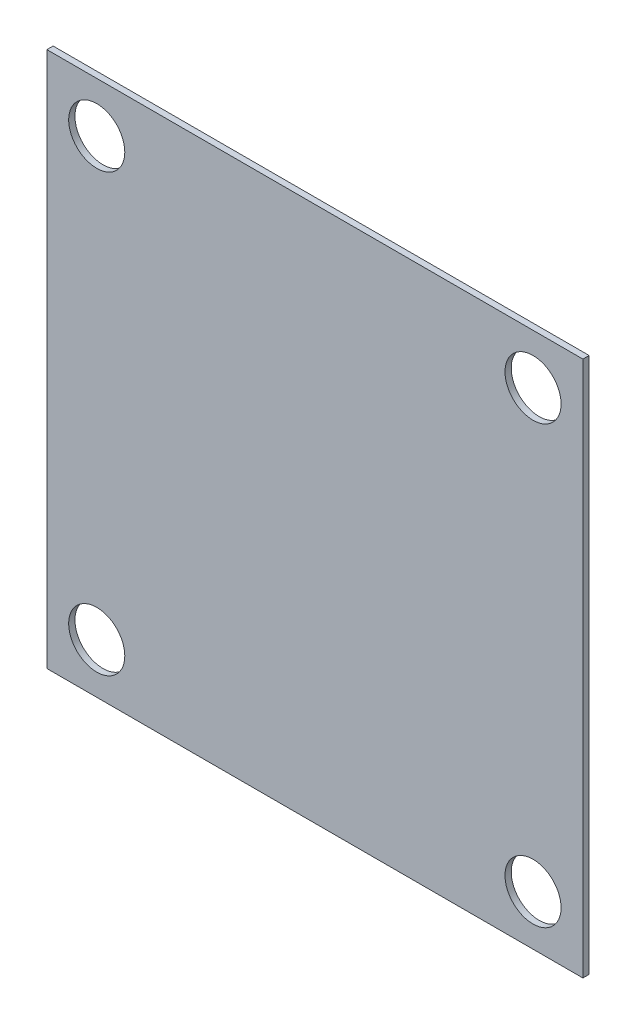
SolidWorks part; units mm, degrees
ref_plane "Front Plane" through (0, 0, 0) normal (0, 0, 1) x (1, 0, 0)
ref_plane "Top Plane" through (0, 0, 0) normal (0, 1, 0) x (1, 0, 0)
ref_plane "Right Plane" through (0, 0, 0) normal (1, 0, 0) x (0, 0, -1)
sketch "Sketch1" plane through (0, 0, 0) normal (0, 0, 1) x (1, 0, 0)
  line L1 (-35, -35) -> (35, -35) construction
  line L2 (-35, -35) -> (-35, 35) construction
  line L3 (-35, 35) -> (35, 35) construction
  line L4 (35, -35) -> (35, 35) construction
  line L5 (-35, -35) -> (35, 35) construction
  line L6 (-35, 35) -> (35, -35) construction
  line L7 (-43, -43) -> (43, -43)
  line L8 (-43, -43) -> (-43, 43)
  line L9 (-43, 43) -> (43, 43)
  line L10 (43, -43) -> (43, 43)
  line L11 (-43, -43) -> (43, 43) construction
  line L12 (-43, 43) -> (43, -43) construction
  circle A0 centre (35, 35) radius 4.5
  circle A1 centre (35, -35) radius 4.5
  circle A2 centre (-35, 35) radius 4.5
  circle A3 centre (-35, -35) radius 4.5
  point P0 (0, 0)
  point P12 (0, 0)
  dimension "D2" = 9
  dimension "D1" = 70
  dimension "D3" = 8
extrude "Boss-Extrude1" add sketch "Sketch1" along normal blind 1
